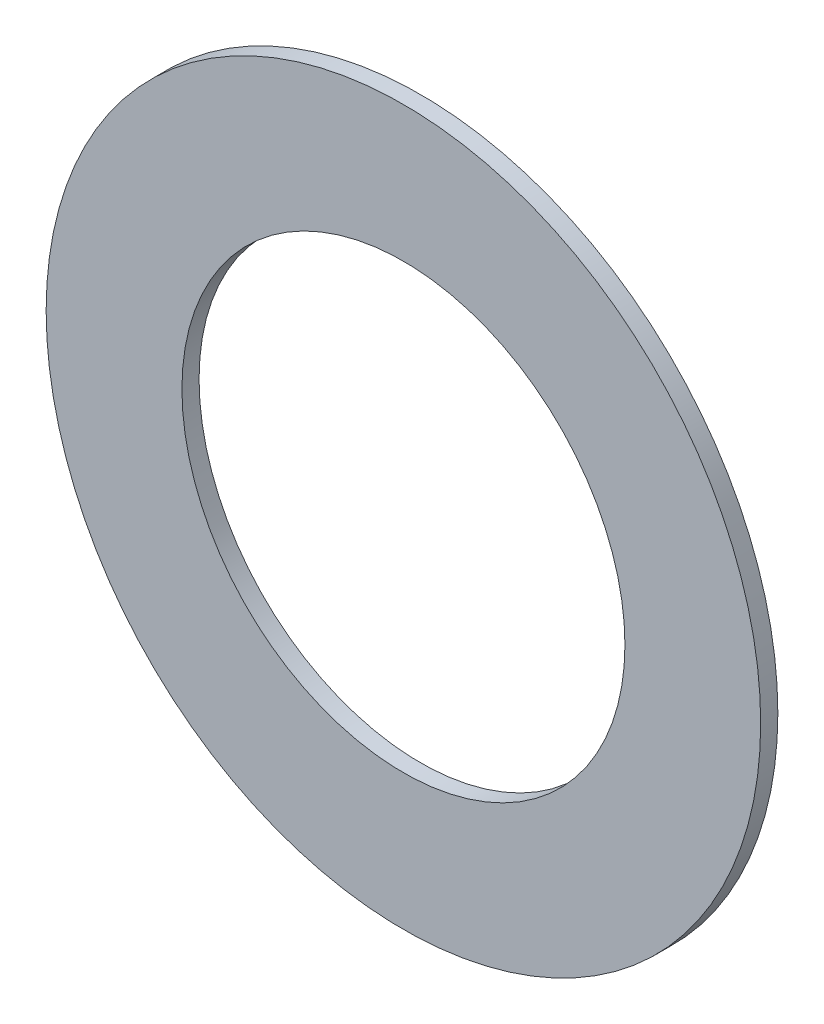
SolidWorks part; units mm, degrees
material "Plain Carbon Steel"
ref_plane "Front Plane" through (0, 0, 0) normal (0, 0, 1) x (1, 0, 0)
ref_plane "Top Plane" through (0, 0, 0) normal (0, 1, 0) x (1, 0, 0)
ref_plane "Right Plane" through (0, 0, 0) normal (1, 0, 0) x (0, 0, -1)
sketch "Sketch1" plane through (0, 0, 0) normal (0, 0, 1) x (1, 0, 0)
  circle A0 centre (0, 0) radius 63.5
  circle A1 centre (0, 0) radius 39.37
  dimension "D1" = 127
  dimension "D2" = 78.74
extrude "Boss-Extrude1" add sketch "Sketch1" along normal blind 3.048
